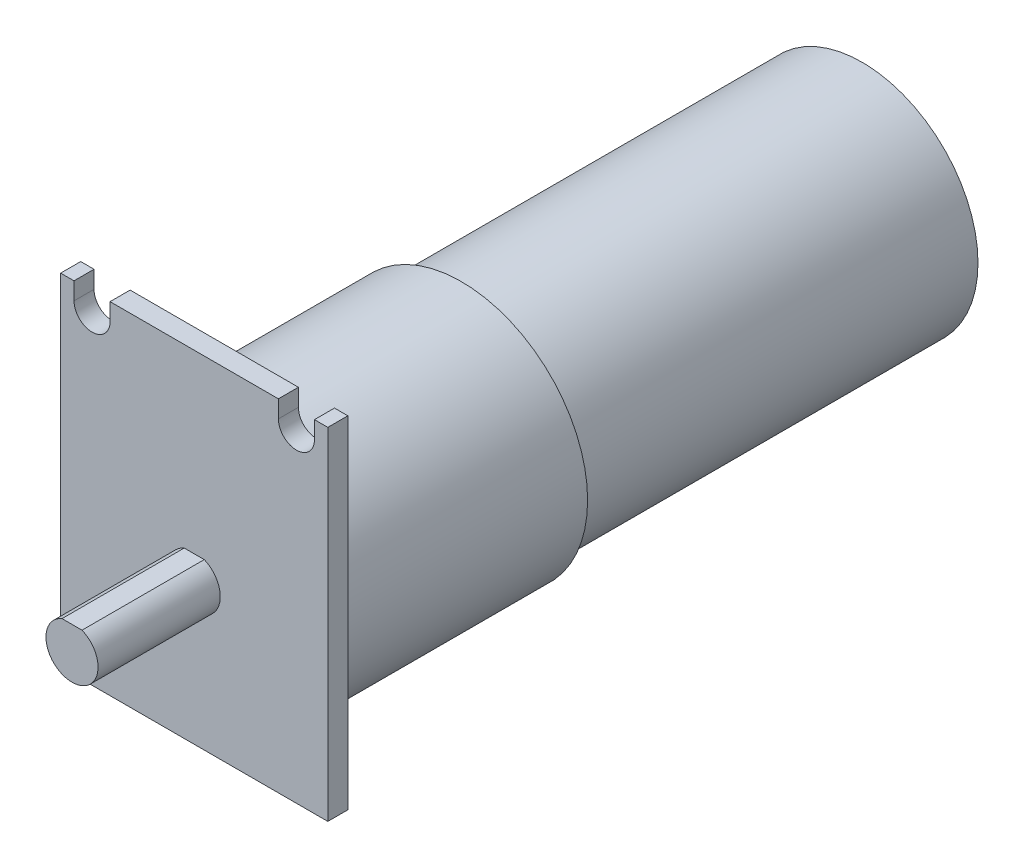
SolidWorks part; units mm, degrees
ref_plane "Front Plane" through (0, 0, 0) normal (0, 0, 1) x (1, 0, 0)
ref_plane "Top Plane" through (0, 0, 0) normal (0, 1, 0) x (1, 0, 0)
ref_plane "Right Plane" through (0, 0, 0) normal (1, 0, 0) x (0, 0, -1)
sketch "Sketch1" plane through (0, 0, 0) normal (0, 0, 1) x (1, 0, 0)
  circle A0 centre (0, 0) radius 17.35
  dimension "D1" = 34.7
extrude "Boss-Extrude1" add sketch "Sketch1" along normal blind 60
sketch "Sketch2" plane through (0, 0, 60) normal (0, 0, 1) x (1, 0, 0)
  circle A0 centre (0, 0) radius 18.9
  dimension "D1" = 37.8
extrude "Boss-Extrude2" add sketch "Sketch2" along normal blind 37
sketch "Sketch4" plane through (0, 0, 97) normal (0, 0, 1) x (1, 0, 0)
  line L0 (0, 0) -> (0, -21.1)
  line L2 (20, 21.1) -> (20, -21.1)
  line L3 (20, -21.1) -> (-20, -21.1)
  line L4 (-20, 21.1) -> (-20, -21.1)
  line L5 (20, 21.1) -> (-20, -21.1) construction
  line L6 (20, -21.1) -> (-20, 21.1) construction
  line L7 (0, 0) -> (0, 30)
  line L8 (-20, 21.1) -> (-20, 30)
  line L10 (20, 30) -> (20, 21.1)
  line L11 (20, 30) -> (18, 30)
  line L12 (18, 30) -> (18, 27.4)
  line L13 (12.6, 27.4) -> (12.6, 30)
  line L14 (12.6, 30) -> (-12.6, 30)
  line L15 (-18, 30) -> (-18, 27.4)
  line L16 (-20, 30) -> (-18, 30)
  line L17 (-12.6, 27.4) -> (-12.6, 30)
  arc A0 (12.6, 27.4) -> (18, 27.4) centre (15.3, 27.4) ccw
  arc A1 (-12.6, 27.4) -> (-18, 27.4) centre (-15.3, 27.4) cw
  point P0 (0, 0)
  dimension "D1" = 40
  dimension "D2" = 21.1
  dimension "D3" = 21.1
  dimension "D4" = 30
  dimension "D5" = 2
  dimension "D6" = 2.6
  dimension "D7" = 5.4
extrude "Boss-Extrude4" add sketch "Sketch4" along normal blind 3 contours L4 L3 L2 L10 L11 L12 A0 L13 L14 L17 A1 L15 L16 L8
sketch "Sketch3" plane through (0, 0, 97) normal (0, 0, 1) x (1, 0, 0)
  line L0 (0, 0) -> (0, 0.4338)
  line L1 (0, 0.4338) -> (0, 0)
  line L2 (0, 3.6) -> (1.5, 3.6)
  line L3 (0, 3.6) -> (-1.5, 3.6)
  arc A0 (-1.5, 3.6) -> (1.5, 3.6) centre (0, 0) ccw
  dimension "D1" = 7.8
  dimension "D2" = 3.6
extrude "Boss-Extrude3" add sketch "Sketch3" along normal blind 21.3
sketch "Sketch5" plane through (0, 0, 100) normal (0, 0, 1) x (1, 0, 0)
  line L0 (-12.6, 30) -> (12.6, 30)
